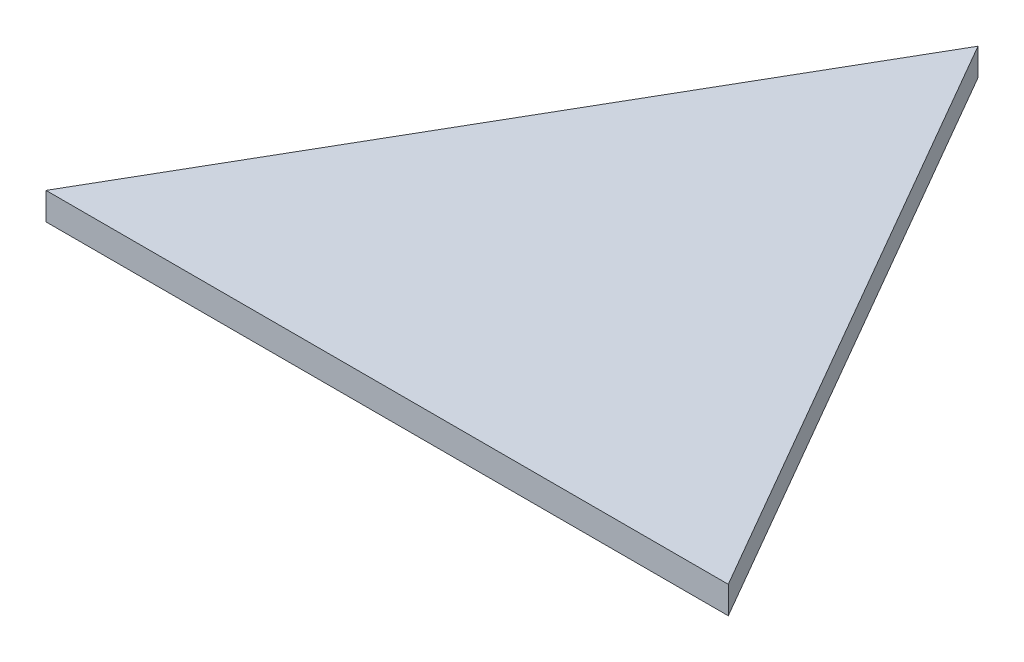
SolidWorks part; units mm, degrees
ref_plane "Front Plane" through (0, 0, 0) normal (0, 0, 1) x (1, 0, 0)
ref_plane "Top Plane" through (0, 0, 0) normal (0, 1, 0) x (1, 0, 0)
ref_plane "Right Plane" through (0, 0, 0) normal (1, 0, 0) x (0, 0, -1)
sketch "Sketch1" plane through (0, 0, 0) normal (0, 1, 0) x (1, 0, 0)
  line L0 (0, 0) -> (50, 0)
  line L1 (50, 0) -> (25, 43.3013)
  line L2 (25, 43.3013) -> (0, 0)
  dimension "D1" = 50
extrude "Boss-Extrude1" add sketch "Sketch1" along normal blind 2
equation "\"length\" = 50mm'side of triangle"
equation "\"thick\"= 2mm'thickness"
equation "\"D1@Sketch1\"=\"length\""
equation "\"D1@Boss-Extrude1\"=\"thick\""
